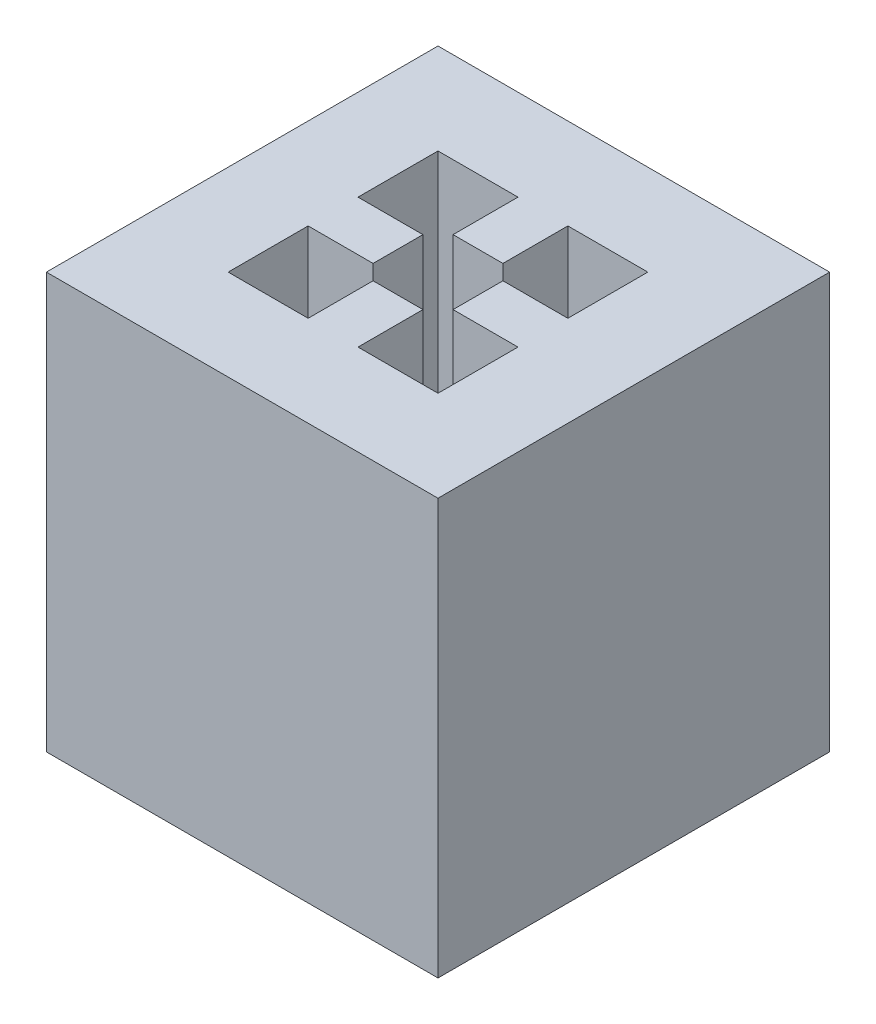
SolidWorks part; units mm, degrees
ref_plane "Plan de face" through (0, 0, 0) normal (0, 0, 1) x (1, 0, 0)
ref_plane "Plan de dessus" through (0, 0, 0) normal (0, 1, 0) x (1, 0, 0)
ref_plane "Plan de droite" through (0, 0, 0) normal (1, 0, 0) x (0, 0, -1)
sketch "Esquisse1" plane through (0, 0, 0) normal (0, 1, 0) x (1, 0, 0)
  line L0 (-10.1, -10.1) -> (10.1, 10.1) construction
  line L7 (-10.1, 10.1) -> (10.1, -10.1) construction
  line L63 (-10.1, 10.1) -> (-2.4, 10.1)
  line L70 (-2.4, 10.1) -> (-2.4, 3.85)
  line L71 (-2.4, 3.85) -> (2.4, 3.85)
  line L72 (2.4, 3.85) -> (2.4, 10.1)
  line L73 (2.4, 10.1) -> (10.1, 10.1)
  line L74 (10.1, 10.1) -> (10.1, 2.4)
  line L75 (10.1, 2.4) -> (3.85, 2.4)
  line L76 (3.85, -2.4) -> (3.85, 2.4)
  line L77 (10.1, -2.4) -> (3.85, -2.4)
  line L78 (10.1, -10.1) -> (10.1, -2.4)
  line L79 (2.4, -10.1) -> (10.1, -10.1)
  line L80 (2.4, -3.85) -> (2.4, -10.1)
  line L81 (-2.4, -3.85) -> (2.4, -3.85)
  line L82 (-2.4, -10.1) -> (-2.4, -3.85)
  line L83 (-10.1, -10.1) -> (-2.4, -10.1)
  line L84 (-10.1, -2.4) -> (-10.1, -10.1)
  line L85 (-3.85, -2.4) -> (-10.1, -2.4)
  line L86 (-3.85, 2.4) -> (-3.85, -2.4)
  line L87 (-10.1, 2.4) -> (-3.85, 2.4)
  line L88 (-10.1, 2.4) -> (-10.1, 10.1)
  line L91 (-18.85, 18.85) -> (18.85, -18.85) construction
  line L92 (-18.85, -18.85) -> (18.85, 18.85) construction
  line L125 (-18.85, 18.85) -> (18.85, 18.85) construction
  line L126 (-18.85, 18.85) -> (-18.85, -18.85) construction
  line L127 (-18.85, -18.85) -> (18.85, -18.85) construction
  line L128 (18.85, 18.85) -> (18.85, -18.85) construction
  line L129 (-18.85, 18.85) -> (18.85, -18.85) construction
  line L130 (-18.85, -18.85) -> (18.85, 18.85) construction
  line L131 (-18.85, 18.85) -> (18.85, 18.85)
  line L132 (-18.85, 18.85) -> (-18.85, -18.85)
  line L133 (-18.85, -18.85) -> (18.85, -18.85)
  line L134 (18.85, 18.85) -> (18.85, -18.85)
  line L135 (-18.85, 18.85) -> (18.85, -18.85) construction
  line L136 (-18.85, -18.85) -> (18.85, 18.85) construction
  point P0 (0, 0)
  point P5 (0, 0)
  point P29 (0, 0)
extrude "Boss.-Extru.1" add sketch "Esquisse1" along normal blind 40
hole_wizard "Chambrage pour vis à tête ronde bombée M31" positions "Esquisse2" profile "Esquisse3" counterbore size "M3" standard "Ansi Metric"
sketch "Esquisse2" plane through (-18.85, 0, 0) normal (-1, 0, 0) x (0, 0, 1)
  point P0 (26.35, 5)
sketch "Esquisse3" plane through (-18.85, 5, 26.35) normal (0, 1, 0) x (0, 0, 1)
  line L0 (0, 0) -> (0, 37.7)
  line L1 (0, 37.7) -> (1.7, 37.7)
  line L3 (1.7, 37.7) -> (1.7, 8)
  line L4 (1.7, 8) -> (3.5, 8)
  line L5 (3.5, 8) -> (3.5, 0)
  line L7 (3.5, 0) -> (0, 0)
  line L11 (0, -6.35) -> (0, 107.95) construction
  dimension "Diamètre du perçage jusqu'au prochain" = 3.4
  dimension "Profondeur du perçage jusqu'au prochain" = 37.7
  dimension "Diamètre du chambrage" = 7
  dimension "Profondeur du chambrage" = 8
mirror "Symétrie1" about plane through (0, 0, 0) normal (0, 0, 1)
hole_wizard "Chambrage pour vis à tête ronde bombée M32" positions "Esquisse5" profile "Esquisse6" counterbore size "M3" standard "Ansi Metric"
sketch "Esquisse5" plane through (0, 0, 18.85) normal (0, 0, 1) x (1, 0, 0)
  point P0 (-26.35, 5)
  point P2 (26.35, 5)
sketch "Esquisse6" plane through (-26.35, 5, 18.85) normal (1, 0, 0) x (0, -1, 0)
  line L0 (0, 0) -> (0, 52.7)
  line L1 (0, 52.7) -> (1.7, 52.7)
  line L3 (1.7, 52.7) -> (1.7, 8)
  line L4 (1.7, 8) -> (3.5, 8)
  line L5 (3.5, 8) -> (3.5, 0)
  line L7 (3.5, 0) -> (0, 0)
  line L11 (0, -6.35) -> (0, 107.95) construction
  dimension "Diamètre du perçage jusqu'au prochain" = 3.4
  dimension "Profondeur du perçage jusqu'au prochain" = 52.7
  dimension "Diamètre du chambrage" = 7
  dimension "Profondeur du chambrage" = 8
